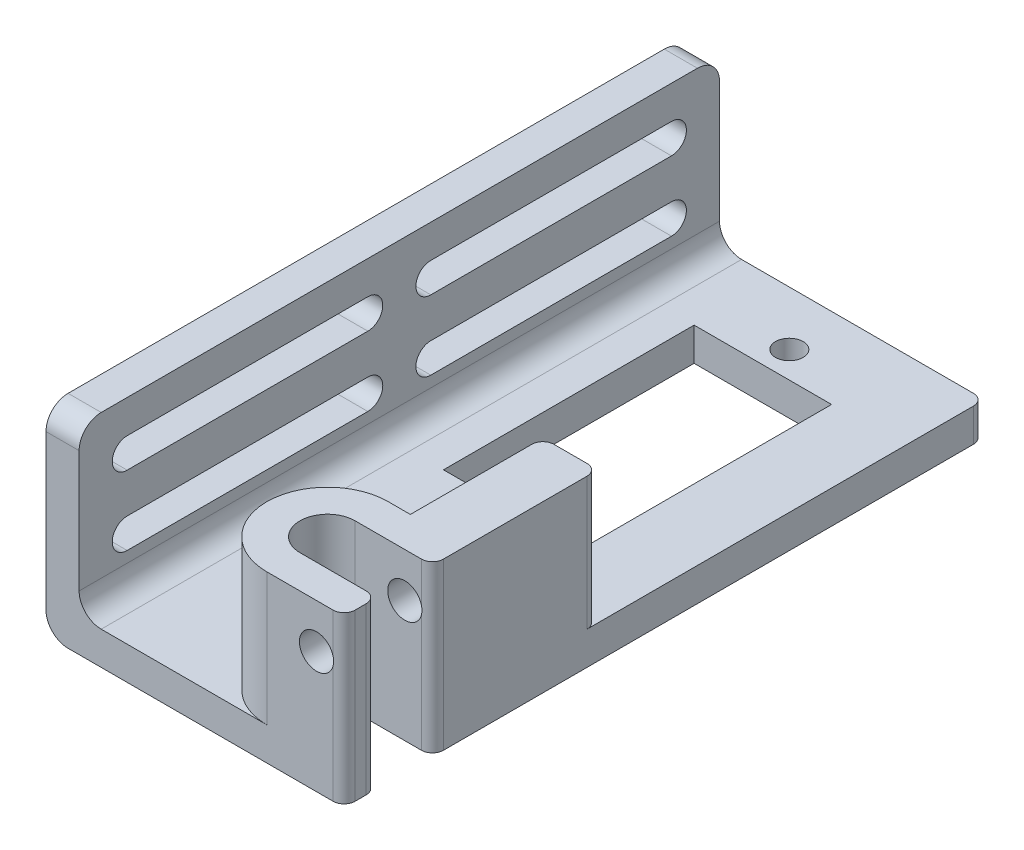
SolidWorks part; units mm, degrees
ref_plane "Front Plane" through (0, 0, 0) normal (0, 0, 1) x (1, 0, 0)
ref_plane "Top Plane" through (0, 0, 0) normal (0, 1, 0) x (1, 0, 0)
ref_plane "Right Plane" through (0, 0, 0) normal (1, 0, 0) x (0, 0, -1)
sketch "Sketch1" plane through (0, 0, 0) normal (0, 1, 0) x (1, 0, 0)
  line L0 (27, 8) -> (20, 8)
  line L1 (0, 0) -> (27, 0)
  line L2 (0, 0) -> (0, 58)
  line L3 (0, 58) -> (27, 58)
  line L4 (27, 0) -> (27, 3)
  line L5 (27, 3) -> (20, 3)
  line L6 (20, 8) -> (20, 3) construction
  line L7 (27, 8) -> (27, 58)
  arc A0 (20, 3) -> (20, 8) centre (20, 5.5) cw
  dimension "D1" = 58
  dimension "D2" = 27
  dimension "D3" = 5
  dimension "D4" = 3
  dimension "D5" = 7
extrude "Boss-Extrude1" add sketch "Sketch1" along normal blind 3
sketch "Sketch2" plane through (0, 3, 0) normal (0, 1, 0) x (1, 0, 0)
  line L0 (0, 58) -> (0, 0) construction
  line L1 (8, 50.7) -> (20.45, 50.7)
  line L2 (8, 50.7) -> (8, 28)
  line L3 (8, 28) -> (20.45, 28)
  line L4 (20.45, 50.7) -> (20.45, 28)
  line L5 (0, 0) -> (27, 0) construction
  line L6 (14.225, 50.7) -> (14.225, 58) construction
  line L7 (27, 58) -> (0, 58) construction
  circle A1 centre (14.225, 53.1) radius 1.25
  circle A2 centre (14.225, 25.6) radius 1.25
  dimension "D4" = 2.5
  dimension "D5" = 2.5
  dimension "D1" = 12.45
  dimension "D2" = 22.7
  dimension "D3" = 8
  dimension "D6" = 2.4
  dimension "D7" = 2.4
  dimension "D8" = 28
extrude "Cut-Extrude1" cut sketch "Sketch2" against normal blind 3
sketch "Sketch3" plane through (0, 3, 0) normal (0, 1, 0) x (1, 0, 0)
  line L0 (0, 0) -> (27, 0) construction
  line L1 (0, 58) -> (3, 58)
  line L2 (0, 58) -> (0, 0)
  line L3 (0, 0) -> (3, 0)
  line L4 (3, 58) -> (3, 0)
  dimension "D1" = 3
extrude "Boss-Extrude2" add sketch "Sketch3" along normal blind 15
sketch "Sketch4" plane through (0, 3, 0) normal (0, 1, 0) x (1, 0, 0)
  line L0 (3, 0) -> (27, 0) construction
  line L1 (20, 11) -> (22, 11)
  line L2 (27, 8) -> (27, 58) construction
  line L3 (20, 8) -> (27, 8) construction
  line L4 (20, 0) -> (27, 0)
  line L5 (27, 0) -> (27, 3)
  line L6 (27, 3) -> (20, 3)
  line L7 (27, 11) -> (27, 8)
  line L8 (27, 8) -> (20, 8)
  line L11 (27, 11) -> (27, 23)
  line L12 (27, 23) -> (22, 23)
  line L13 (22, 11) -> (22, 23)
  arc A0 (20, 0) -> (20, 11) centre (20, 5.5) cw
  arc A1 (20, 8) -> (20, 3) centre (20, 5.5) ccw construction
  arc A2 (20, 8) -> (20, 3) centre (20, 5.5) ccw
  dimension "D1" = 3
  dimension "D2" = 3
  dimension "D3" = 5
  dimension "D4" = 12
extrude "Boss-Extrude3" add sketch "Sketch4" along normal blind 12
fillet "Fillet1" radius 2 2 edges at (3, 3, -29) (0, 0, -29)
fillet "Fillet2" radius 2 2 edges at (1.5, 18, -58) (1.5, 18, 0)
fillet "Fillet3" radius 1 6 edges at (27, 9, -23) (22, 9, -23) (27, 7.5, -8) (27, 7.5, -3) (27, 7.5, 0) (27, 1.5, -58)
sketch "Sketch5" plane through (0, 0, 0) normal (-1, 0, 0) x (0, 0, 1)
  line L0 (-53.65, 13.65) -> (-31.85, 13.65) construction
  line L1 (-53.65, 15) -> (-31.85, 15)
  line L2 (-53.65, 12.3) -> (-31.85, 12.3)
  line L3 (-53.65, 7.35) -> (-31.85, 7.35) construction
  line L4 (-53.65, 8.7) -> (-31.85, 8.7)
  line L5 (-53.65, 6) -> (-31.85, 6)
  line L6 (-56, 18) -> (-2, 18) construction
  line L7 (-58, 2) -> (0, 2) construction
  line L8 (-26.15, 13.65) -> (-4.35, 13.65) construction
  line L9 (-26.15, 15) -> (-4.35, 15)
  line L10 (-26.15, 12.3) -> (-4.35, 12.3)
  line L11 (-26.15, 7.35) -> (-4.35, 7.35) construction
  line L12 (-26.15, 8.7) -> (-4.35, 8.7)
  line L13 (-26.15, 6) -> (-4.35, 6)
  line L14 (-58, 16) -> (-58, 2) construction
  line L15 (0, 16) -> (0, 2) construction
  line L16 (-29, 18) -> (-29, 2) construction
  arc A0 (-53.65, 15) -> (-53.65, 12.3) centre (-53.65, 13.65) ccw
  arc A1 (-31.85, 12.3) -> (-31.85, 15) centre (-31.85, 13.65) ccw
  arc A2 (-53.65, 8.7) -> (-53.65, 6) centre (-53.65, 7.35) ccw
  arc A3 (-31.85, 6) -> (-31.85, 8.7) centre (-31.85, 7.35) ccw
  arc A4 (-26.15, 15) -> (-26.15, 12.3) centre (-26.15, 13.65) ccw
  arc A5 (-4.35, 12.3) -> (-4.35, 15) centre (-4.35, 13.65) ccw
  arc A6 (-26.15, 8.7) -> (-26.15, 6) centre (-26.15, 7.35) ccw
  arc A7 (-4.35, 6) -> (-4.35, 8.7) centre (-4.35, 7.35) ccw
  point P2 (-42.75, 13.65)
  point P9 (-42.75, 7.35)
  point P20 (-15.25, 13.65)
  point P25 (-15.25, 7.35)
  point P34 (-55, 13.65)
  point P35 (-55, 7.35)
  point P36 (-3, 13.65)
  point P39 (-3, 7.35)
  point P40 (-30.5, 13.65)
  point P41 (-30.5, 7.35)
  point P42 (-27.5, 13.65)
  point P43 (-27.5, 7.35)
  dimension "D8" = 3
  dimension "D1" = 2.7
  dimension "D2" = 2.7
  dimension "D3" = 3
  dimension "D4" = 4
  dimension "D5" = 2.7
  dimension "D6" = 2.7
  dimension "D7" = 3
  dimension "D9" = 3
  dimension "D10" = 3
  dimension "D11" = 1.5
  dimension "D12" = 1.5
  dimension "D13" = 1.5
  dimension "D14" = 1.5
extrude "Cut-Extrude2" cut sketch "Sketch5" against normal blind 3
sketch "Sketch7" plane through (0, 0, -23) normal (0, 0, -1) x (-1, 0, 0)
  line L0 (-24.5, 15) -> (-24.5, 3) construction
  line L1 (-26, 15) -> (-23, 15) construction
  line L2 (-26, 3) -> (-23, 3) construction
  circle A0 centre (-24.5, 11) radius 1.55
  dimension "D1" = 3.1
  dimension "D2" = 4
extrude "Cut-Extrude3" cut sketch "Sketch7" against normal through all
